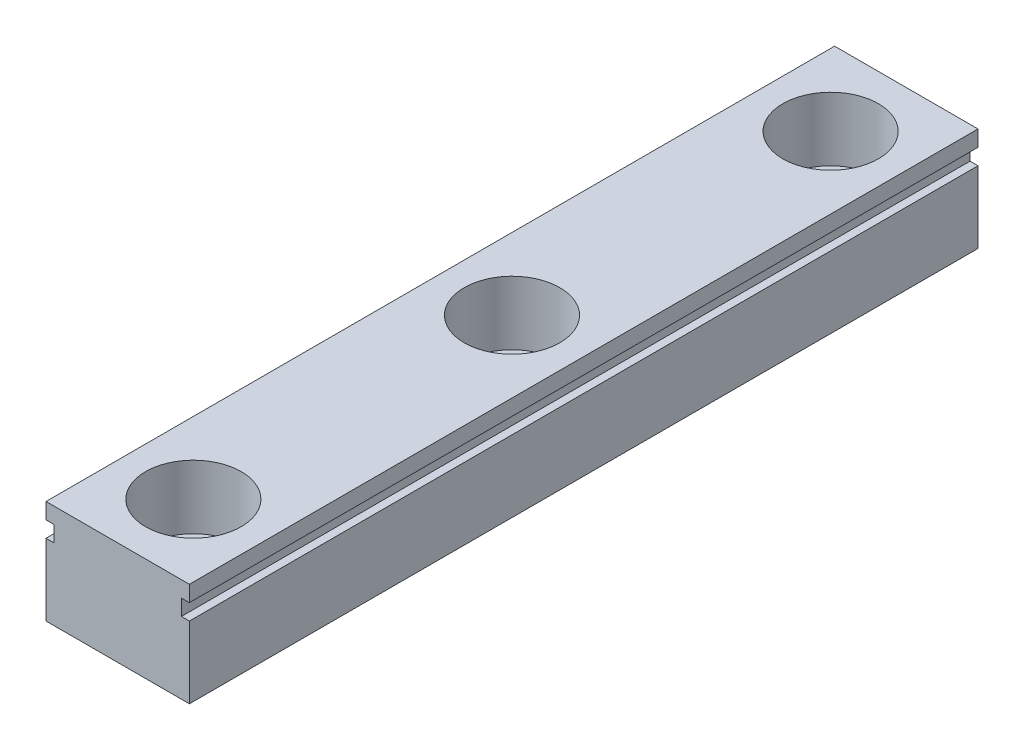
SolidWorks part; units mm, degrees
ref_plane "前视基准面" through (0, 0, 0) normal (0, 0, 1) x (1, 0, 0)
ref_plane "上视基准面" through (0, 0, 0) normal (0, 1, 0) x (1, 0, 0)
ref_plane "右视基准面" through (0, 0, 0) normal (1, 0, 0) x (0, 0, -1)
other "Configuration Table"
sketch "草图1" plane through (0, 0, 0) normal (0, 1, 0) x (1, 0, 0)
  line L1 (0, 0) -> (9, 0)
  line L2 (0, 0) -> (0, -49.5)
  line L3 (0, -49.5) -> (9, -49.5)
  line L4 (9, 0) -> (9, -49.5)
  dimension "D1" = 9
  dimension "D2" = 49.5
extrude "凸台-拉伸1" add sketch "草图1" along normal blind 6.5
sketch "草图2" plane through (0, 6.5, 0) normal (0, 1, 0) x (1, 0, 0)
  line L0 (9, -49.5) -> (9, 0) construction
  circle A0 centre (4.5, -24.75) radius 1.55
  circle A1 centre (4.5, -4.75) radius 1.55
  circle A2 centre (4.5, -44.75) radius 1.55
  point P6 (9, -24.75)
  point P8 (4.0853, -24.1872)
  dimension "D1" = 3.1
  dimension "D2" = 3.1
  dimension "D4" = 3.1
  dimension "D3" = 20
  dimension "D5" = 20
  dimension "D6" = 0
extrude "切除-拉伸1" cut sketch "草图2" against normal through all
sketch "草图3" plane through (0, 6.5, 0) normal (0, 1, 0) x (1, 0, 0)
  circle A0 centre (4.5, -44.75) radius 3
  circle A1 centre (4.5, -24.75) radius 3
  circle A2 centre (4.5, -4.75) radius 3
  dimension "D1" = 6
  dimension "D2" = 6
  dimension "D3" = 6
extrude "切除-拉伸2" cut sketch "草图3" against normal blind 4
sketch "草图4" plane through (0, 0, 49.5) normal (0, 0, 1) x (1, 0, 0)
  line L0 (0, 6.5) -> (0, 0) construction
  line L1 (0, 5.5) -> (0.5, 5.5)
  line L2 (0, 5.5) -> (0, 4.5)
  line L3 (0, 4.5) -> (0.5, 4.5)
  line L4 (0.5, 5.5) -> (0.5, 4.5)
  line L5 (9, 6.5) -> (9, 0) construction
  line L6 (9, 5.5) -> (8.5, 5.5)
  line L7 (9, 5.5) -> (9, 4.5)
  line L8 (9, 4.5) -> (8.5, 4.5)
  line L9 (8.5, 5.5) -> (8.5, 4.5)
  line L10 (0, 6.5) -> (9, 6.5) construction
  dimension "D1" = 1
  dimension "D2" = 1
  dimension "D3" = 1
  dimension "D4" = 1
  dimension "D5" = 0.5
  dimension "D6" = 0.5
extrude "切除-拉伸3" cut sketch "草图4" against normal through all
